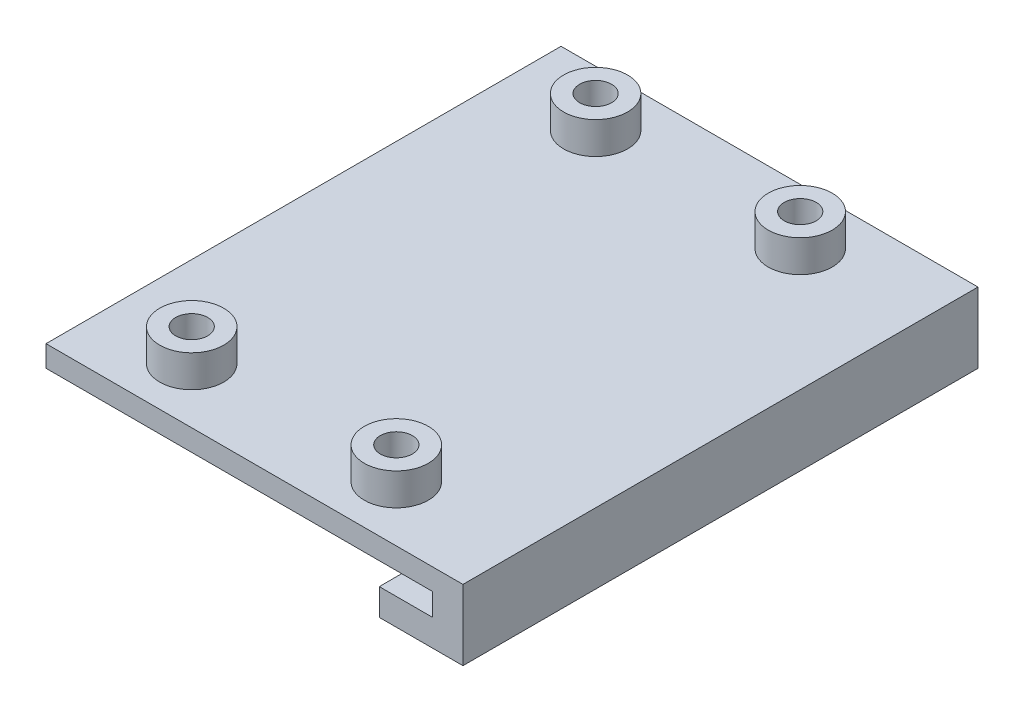
SolidWorks part; units mm, degrees
ref_plane "Front Plane" through (0, 0, 0) normal (0, 0, 1) x (1, 0, 0)
ref_plane "Top Plane" through (0, 0, 0) normal (0, 1, 0) x (1, 0, 0)
ref_plane "Right Plane" through (0, 0, 0) normal (1, 0, 0) x (0, 0, -1)
sketch "Esquisse1" plane through (0, 0, 0) normal (0, 1, 0) x (1, 0, 0)
  line L1 (-18.034, 24.13) -> (18.034, 24.13)
  line L2 (-18.034, 24.13) -> (-18.034, -24.13)
  line L3 (-18.034, -24.13) -> (18.034, -24.13)
  line L4 (18.034, 24.13) -> (18.034, -24.13)
  line L5 (-18.034, 24.13) -> (18.034, -24.13) construction
  line L6 (-18.034, -24.13) -> (18.034, 24.13) construction
  point P0 (0, 0)
extrude "Boss.-Extru.1" add sketch "Esquisse1" along normal blind 2
ref_plane "Plan1" through (0, 0, 0) normal (1, 0, 0) x (0, 0, -1)
sketch "Esquisse4" plane through (0, 2, 0) normal (0, 1, 0) x (1, 0, 0)
  line L1 (18.034, -24.13) -> (18.034, 24.13) construction
  circle A0 centre (9.5857, 18.921) radius 3
  circle A1 centre (9.5857, -18.925) radius 3
  point P7 (18.034, 0)
  dimension "D1" = 37.846
  dimension "D2" = 18.925
extrude "Boss.-Extru.2" add sketch "Esquisse4" along normal blind 3
sketch "Esquisse6" plane through (0, 5, 0) normal (0, 1, 0) x (1, 0, 0)
  circle A0 centre (9.5857, 18.921) radius 1.5
  circle A1 centre (9.5857, -18.925) radius 1.5
extrude "Enlèv. mat.-Extru.1" cut sketch "Esquisse6" against normal through all
mirror "Symétrie1" about plane through (0, 0, 0) normal (1, 0, 0) of "Boss.-Extru.2", "Enlèv. mat.-Extru.1"
sketch "Esquisse10" plane through (18.034, 0, 0) normal (1, 0, 0) x (0, 0, -1)
  line L1 (24.13, 2) -> (-24.13, 2)
  line L2 (24.13, 2) -> (24.13, 0)
  line L3 (24.13, 0) -> (-24.13, 0)
  line L4 (-24.13, 2) -> (-24.13, 0)
extrude "Boss.-Extru.3" add sketch "Esquisse10" along normal blind 3
sketch "Esquisse11" plane through (0, 0, 0) normal (0, -1, 0) x (-1, 0, 0)
  line L0 (18.034, -24.13) -> (-21.034, -24.13) construction
  line L1 (-21.034, 24.13) -> (-18.1944, 24.13)
  line L2 (-21.034, 24.13) -> (-21.034, -24.13)
  line L3 (-21.034, -24.13) -> (-18.1944, -24.13)
  line L4 (-18.1944, 24.13) -> (-18.1944, -24.13)
extrude "Boss.-Extru.4" add sketch "Esquisse11" along normal blind 4.6
sketch "Esquisse12" plane through (18.1944, 0, 0) normal (-1, 0, 0) x (0, 0, 1)
  line L0 (-24.13, -4.6) -> (-24.13, 0) construction
  line L1 (24.13, -4.6) -> (-24.13, -4.6)
  line L2 (24.13, -4.6) -> (24.13, -2.1)
  line L3 (24.13, -2.1) -> (-24.13, -2.1)
  line L4 (-24.13, -4.6) -> (-24.13, -2.1)
extrude "Boss.-Extru.5" add sketch "Esquisse12" along normal blind 5
